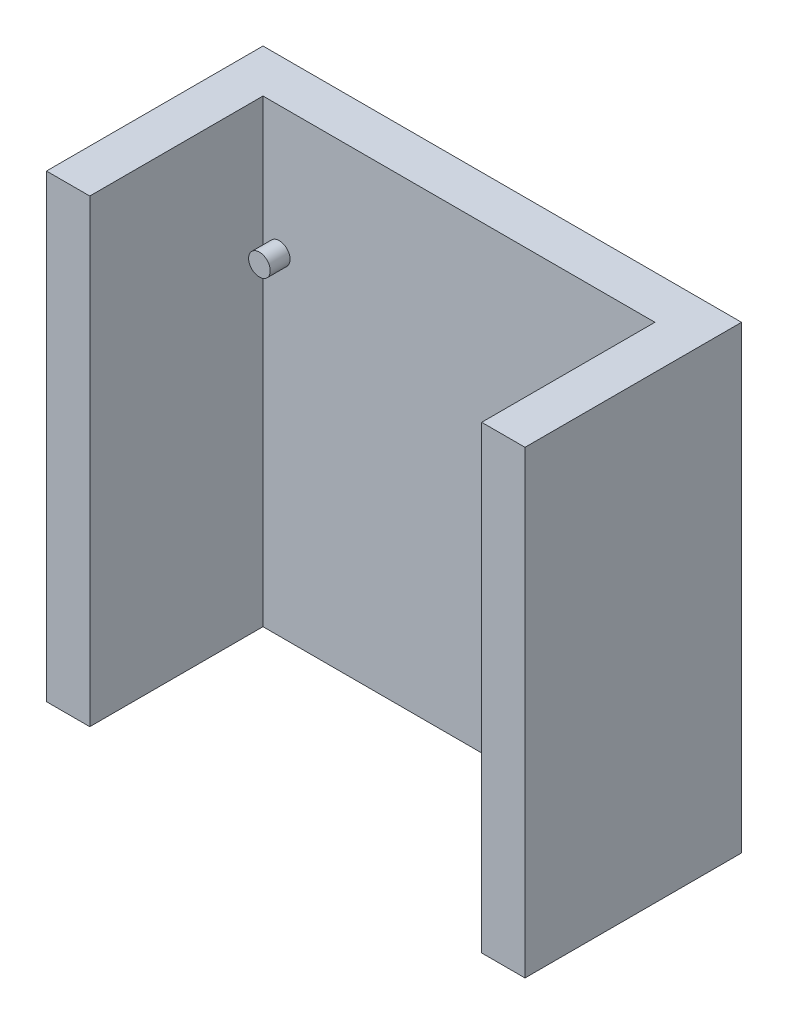
SolidWorks part; units mm, degrees
ref_plane "Front Plane" through (0, 0, 0) normal (0, 0, 1) x (1, 0, 0)
ref_plane "Top Plane" through (0, 0, 0) normal (0, 1, 0) x (1, 0, 0)
ref_plane "Right Plane" through (0, 0, 0) normal (1, 0, 0) x (0, 0, -1)
sketch "Sketch1" plane through (0, 0, 0) normal (1, 0, 0) x (0, 0, -1)
  line L0 (-145, 145) -> (-145, 255)
  line L2 (-145, 0) -> (-145, 145)
  line L3 (-145, 145) -> (0, 145) construction
  line L4 (0, 0) -> (0, 145)
  line L5 (-145, 255) -> (0, 255)
  line L6 (0, 255) -> (0, 145)
  line L7 (0, -145) -> (420.2376, 355.8197) construction
  line L8 (0, -145) -> (-93.2042, -33.9236) construction
  line L9 (94.1529, -32.793) -> (175.1688, -32.793) construction
  line L10 (-93.2042, -33.9236) -> (741.3522, 221.2259) construction
  line L11 (301.5271, 86.7579) -> (438.6224, 86.7579) construction
  line L12 (0, -145) -> (-176.7331, -199.0327) construction
  line L13 (-93.2042, -33.9236) -> (-193.8224, -153.8356) construction
  line L14 (274.6455, 249.3185) -> (274.6455, -80.6815)
  line L15 (274.6455, -80.6815) -> (168.3686, 167.5225)
  arc A0 (0, -145) -> (-145, 0) centre (0, 0) cw
  parabola Q0 (0, 0) -> (300.3031, 267.8046) focus (0, -145) apex (-49.0614, -159.9996)
  parabola Q1 (0, -145) -> (593.7614, 75.583) focus (-93.2042, -33.9236) apex (-147.8987, -99.1059)
  dimension "D1" = 145
  dimension "D2" = 110
  dimension "D3" = 50
  dimension "D4" = 17
  dimension "D5" = 80
  dimension "D6" = 330
  dimension "D7" = 270
sketch "Sketch2" plane through (0, 0, 0) normal (1, 0, 0) x (0, 0, -1)
  line L0 (-145, 145) -> (0, 145) construction
  line L1 (0, 255) -> (0, 145) construction
  line L2 (-145, 255) -> (0, 255) construction
  line L3 (-145, 145) -> (-145, 255) construction
  line L4 (274.6455, -80.6815) -> (168.3686, 167.5225) construction
  line L5 (274.6455, 249.3185) -> (274.6455, -80.6815) construction
  line L6 (0, 0) -> (0, 145) construction
  line L7 (-145, 0) -> (-145, 145) construction
  line L8 (-145, 145) -> (0, 145) construction
  line L9 (0, 255) -> (0, 145)
  line L10 (-145, 255) -> (0, 255)
  line L11 (-145, 145) -> (-145, 255)
  line L12 (274.6455, -80.6815) -> (168.3686, 167.5225)
  line L13 (274.6455, 249.3185) -> (274.6455, -80.6815) construction
  line L14 (0, 0) -> (0, 145)
  line L15 (-145, 0) -> (-145, 145)
  line L16 (-145.6, 0) -> (-145.6, 145)
  line L20 (0.6, 1.8139) -> (0.6, 145)
  line L21 (274.2922, 249.8034) -> (274.6455, 249.3185)
  line L22 (274.6455, -80.6815) -> (274.8642, -81.2403)
  line L23 (168.3686, 167.5225) -> (172.0457, 169.097)
  line L24 (168.3686, 167.5225) -> (274.6455, -80.6815)
  line L25 (172.0457, 169.097) -> (278.3226, -79.1071)
  line L26 (274.6455, -80.6815) -> (278.3226, -79.1071)
  line L27 (0, 145) -> (0.6, 145)
  line L28 (-145, 145) -> (-145.6, 145)
  line L29 (-155, 145) -> (-155, 265)
  line L30 (0.6, 255.6) -> (0.6, 145) construction
  line L31 (-145.6, 255.6) -> (0.6, 255.6) construction
  line L32 (-145.6, 145) -> (-145.6, 255.6) construction
  line L33 (-155, 265) -> (10, 265)
  line L34 (10, 265) -> (10, 145)
  line L35 (-155, 145) -> (-145, 145)
  line L36 (10, 145) -> (0, 145)
  line L38 (0, 145) -> (-145, 145)
  line L39 (0, 145) -> (0, 144.7)
  line L40 (0, 144.7) -> (-145, 144.7)
  line L41 (-145, 145) -> (-145, 144.7)
  arc A0 (-145, 0) -> (0, -145) centre (0, 0) ccw construction
  arc A1 (-145, 0) -> (0, -145) centre (0, 0) ccw
  arc A2 (-145.6, 0) -> (0, -145.6) centre (0, 0) ccw
  parabola Q0 (0, -145) -> (593.7614, 75.583) focus (-93.2042, -33.9236) apex (-147.8987, -99.1059) construction
  parabola Q1 (0, 0) -> (300.3031, 267.8046) focus (0, -145) apex (-49.0614, -159.9996) construction
  parabola Q2 (0, -145) -> (274.6455, -80.6815) focus (-93.2042, -33.9236) apex (-147.8987, -99.1059)
  parabola Q3 (0, 0) -> (274.6455, 249.3185) focus (0, -145) apex (-49.0614, -159.9996)
  spline S0 degree 1 poles (0, -145.6) (274.8642, -81.2403) knots 0 0 1 1 construction
  spline S1 degree 1 poles (0.6, 1.8139) (274.2922, 249.8034) knots 0 0 1 1 construction
  spline S2 degree 3 poles (274.8642, -81.2403) (273.1576, -81.9083) (269.7338, -83.2415) (262.9417, -85.8581) (254.5103, -89.0531) (244.501, -92.7603) (231.2945, -97.5361) (215.05, -103.1917) (195.9774, -109.4761) (177.3259, -115.2579) (153.0186, -122.2971) (123.6866, -129.8396) (90.1715, -136.8804) (63.6442, -141.072) (43.2642, -143.4196) (28.3972, -144.6775) (16.3662, -145.3064) (6.9341, -145.5581) (2.32, -145.6) (0, -145.6) knots 0.50387 0.50387 0.50387 0.50387 0.503942 0.504013 0.504156 0.5043 0.504443 0.504729 0.505015 0.505302 0.505588 0.506161 0.506734 0.507306 0.507593 0.507879 0.508165 0.508308 0.508452 0.508452 0.508452 0.508452
  spline S3 degree 3 poles (0.6, 1.8139) (1.4319, 2.9295) (3.0981, 5.1446) (6.5223, 9.6202) (10.937, 15.2496) (16.4614, 22.0765) (24.1255, 31.2688) (34.2669, 42.9303) (47.3338, 57.1972) (61.2981, 71.7376) (81.1138, 91.4895) (108.1271, 116.8637) (138.1321, 143.1509) (163.9312, 164.7288) (184.1782, 181.1862) (205.3228, 197.9178) (223.6912, 212.0892) (238.8352, 223.5637) (250.4165, 232.2373) (260.2579, 239.5249) (268.2359, 245.3839) (272.2758, 248.3346) (274.2922, 249.8034) knots 0.504877 0.504877 0.504877 0.504877 0.504963 0.505049 0.50522 0.505391 0.505563 0.505905 0.506248 0.50659 0.506933 0.507618 0.508303 0.508646 0.508989 0.509331 0.509674 0.509845 0.510016 0.510188 0.510273 0.510359 0.510359 0.510359 0.510359
  dimension "D2" = 4
  dimension "D4" = 0.3
  dimension "D1" = 0.6
  dimension "D3" = 10
sketch "Sketch3" plane through (0, 0, 0) normal (1, 0, 0) x (0, 0, -1)
  line L0 (274.6455, -80.6815) -> (168.3686, 167.5225) construction
  line L1 (168.3686, 167.5225) -> (172.0457, 169.097) construction
  line L2 (172.0457, 169.097) -> (278.3226, -79.1071) construction
  line L3 (274.6455, -80.6815) -> (278.3226, -79.1071) construction
  line L4 (168.3686, 167.5225) -> (274.6455, -80.6815) construction
  line L5 (0, 255) -> (0, 145) construction
  line L6 (-145, 255) -> (0, 255) construction
  line L7 (-145, 145) -> (-145, 255) construction
  line L8 (-145, 0) -> (-145, 145) construction
  line L9 (-145, 145) -> (-145.6, 145) construction
  line L10 (-145.6, 0) -> (-145.6, 145) construction
  line L11 (274.6455, -80.6815) -> (274.8642, -81.2403) construction
  line L12 (-155, 145) -> (-145, 145) construction
  line L13 (-155, 145) -> (-155, 265) construction
  line L14 (-155, 265) -> (10, 265) construction
  line L15 (10, 265) -> (10, 145) construction
  line L16 (10, 145) -> (0, 145) construction
  line L17 (0, 145) -> (-145, 145) construction
  line L18 (0, 145) -> (0, 144.7) construction
  line L19 (0, 144.7) -> (-145, 144.7) construction
  line L20 (-145, 145) -> (-145, 144.7) construction
  line L21 (0, 0) -> (0, 145) construction
  line L22 (274.2922, 249.8034) -> (274.6455, 249.3185) construction
  line L23 (0.6, 1.8139) -> (0.6, 145) construction
  line L24 (0, 145) -> (0.6, 145) construction
  line L25 (274.6455, -80.6815) -> (168.3686, 167.5225)
  line L26 (168.3686, 167.5225) -> (172.0457, 169.097)
  line L27 (172.0457, 169.097) -> (278.3226, -79.1071)
  line L28 (274.6455, -80.6815) -> (278.3226, -79.1071)
  line L29 (168.3686, 167.5225) -> (274.6455, -80.6815)
  line L30 (0, 255) -> (0, 145)
  line L31 (-145, 255) -> (0, 255)
  line L32 (-145, 145) -> (-145, 255)
  line L33 (-145, 0) -> (-145, 145)
  line L34 (-145, 145) -> (-145.6, 145)
  line L35 (-145.6, 0) -> (-145.6, 145)
  line L36 (274.6455, -80.6815) -> (274.8642, -81.2403)
  line L37 (-155, 145) -> (-145, 145)
  line L38 (-155, 145) -> (-155, 265)
  line L39 (-155, 265) -> (10, 265)
  line L40 (10, 265) -> (10, 145)
  line L41 (10, 145) -> (0, 145)
  line L42 (0, 145) -> (-145, 145)
  line L43 (0, 145) -> (0, 144.7)
  line L44 (0, 144.7) -> (-145, 144.7)
  line L45 (-145, 145) -> (-145, 144.7)
  line L46 (0, 0) -> (0, 145)
  line L47 (274.2922, 249.8034) -> (274.6455, 249.3185)
  line L48 (0.6, 1.8139) -> (0.6, 145)
  line L49 (0, 145) -> (0.6, 145)
  line L50 (-155, 575) -> (-155, 695)
  line L51 (-145, 575) -> (-145, 685)
  line L52 (-155, 695) -> (10, 695)
  line L53 (-145, 685) -> (0, 685)
  line L54 (10, 695) -> (10, 575)
  line L55 (0, 685) -> (0, 575)
  line L56 (10, 575) -> (0, 575)
  line L57 (0.6, 431.8139) -> (0.6, 575)
  line L58 (0, 430) -> (0, 575)
  line L59 (0, 574.7) -> (-145, 574.7)
  line L60 (-145, 430) -> (-145, 575)
  line L61 (-145.6, 430) -> (-145.6, 575)
  line L62 (-155, 575) -> (-145, 575)
  line L63 (274.6455, 349.3185) -> (274.8642, 348.7597)
  line L64 (274.6455, 349.3185) -> (278.3226, 350.8929)
  line L65 (274.6455, 349.3185) -> (168.3686, 597.5225)
  line L66 (172.0457, 599.097) -> (278.3226, 350.8929)
  line L67 (168.3686, 597.5225) -> (172.0457, 599.097)
  line L68 (274.2922, 679.8034) -> (274.6455, 679.3185)
  line L69 (0, 575) -> (-145, 575)
  line L70 (-155, 1005) -> (-155, 1125)
  line L71 (-145, 1005) -> (-145, 1115)
  line L72 (-155, 1125) -> (10, 1125)
  line L73 (-145, 1115) -> (0, 1115)
  line L74 (10, 1125) -> (10, 1005)
  line L75 (0, 1115) -> (0, 1005)
  line L76 (10, 1005) -> (0, 1005)
  line L77 (0.6, 861.8139) -> (0.6, 1005)
  line L78 (0, 860) -> (0, 1005)
  line L79 (0, 1004.7) -> (-145, 1004.7)
  line L80 (-145, 860) -> (-145, 1005)
  line L81 (-145.6, 860) -> (-145.6, 1005)
  line L82 (-155, 1005) -> (-145, 1005)
  line L83 (274.6455, 779.3185) -> (274.8642, 778.7597)
  line L84 (274.6455, 779.3185) -> (278.3226, 780.8929)
  line L85 (274.6455, 779.3185) -> (168.3686, 1027.5225)
  line L86 (172.0457, 1029.097) -> (278.3226, 780.8929)
  line L87 (168.3686, 1027.5225) -> (172.0457, 1029.097)
  line L88 (274.2922, 1109.8034) -> (274.6455, 1109.3185)
  line L89 (0, 1005) -> (-145, 1005)
  arc A0 (-145, 0) -> (0, -145) centre (0, 0) ccw construction
  arc A1 (-145.6, 0) -> (0, -145.6) centre (0, 0) ccw construction
  arc A2 (-145, 0) -> (0, -145) centre (0, 0) ccw
  arc A3 (-145.6, 0) -> (0, -145.6) centre (0, 0) ccw
  arc A4 (-145, 430) -> (0, 285) centre (0, 430) ccw
  arc A5 (-145.6, 430) -> (0, 284.4) centre (0, 430) ccw
  arc A6 (-145, 860) -> (0, 715) centre (0, 860) ccw
  arc A7 (-145.6, 860) -> (0, 714.4) centre (0, 860) ccw
  parabola Q0 (0, -145) -> (274.6455, -80.6815) focus (-93.2042, -33.9236) apex (-147.8987, -99.1059) construction
  parabola Q1 (0, 0) -> (274.6455, 249.3185) focus (0, -145) apex (-49.0614, -159.9996) construction
  parabola Q2 (0, -145) -> (274.6455, -80.6815) focus (-93.2042, -33.9236) apex (-147.8987, -99.1059)
  parabola Q3 (0, 0) -> (274.6455, 249.3185) focus (0, -145) apex (-49.0614, -159.9996)
  parabola Q4 (0, 430) -> (274.6455, 679.3185) focus (0, 285) apex (-49.0614, 270.0004)
  parabola Q5 (0, 285) -> (274.6455, 349.3185) focus (-93.2042, 396.0764) apex (-147.8987, 330.8941)
  parabola Q6 (0, 860) -> (274.6455, 1109.3185) focus (0, 715) apex (-49.0614, 700.0004)
  parabola Q7 (0, 715) -> (274.6455, 779.3185) focus (-93.2042, 826.0764) apex (-147.8987, 760.8941)
  spline S0 degree 3 poles (-2532.6565, -1138.1182) (517.166, 27.2131) (377.0621, -41.8945) (262.9417, -85.8581) (254.5103, -89.0531) (244.501, -92.7603) (231.2945, -97.5361) (215.05, -103.1917) (195.9774, -109.4761) (177.3259, -115.2579) (153.0186, -122.2971) (123.6866, -129.8396) (90.1715, -136.8804) (63.6442, -141.072) (43.2642, -143.4196) (28.3972, -144.6775) (16.3662, -145.3064) (-89.7923, -148.1384) (-144.0863, -112.0401) (-2997.9045, -39.5411) knots 0.499345 0.499345 0.499345 0.499345 0.503942 0.504013 0.504156 0.5043 0.504443 0.504729 0.505015 0.505302 0.505588 0.506161 0.506734 0.507306 0.507593 0.507879 0.508165 0.508308 0.514325 0.514325 0.514325 0.514325 only from (274.8642, -81.2403) to (0, -145.6) construction
  spline S1 degree 3 poles (-1751.4871, -2433.1925) (-55.1342, -100.2952) (-43.2482, -55.4331) (6.5223, 9.6202) (10.937, 15.2496) (16.4614, 22.0765) (24.1255, 31.2688) (34.2669, 42.9303) (47.3338, 57.1972) (61.2981, 71.7376) (81.1138, 91.4895) (108.1271, 116.8637) (138.1321, 143.1509) (163.9312, 164.7288) (184.1782, 181.1862) (205.3228, 197.9178) (223.6912, 212.0892) (238.8352, 223.5637) (250.4165, 232.2373) (260.2579, 239.5249) (377.9568, 325.9622) (533.0374, 426.7515) (-2133.1319, -1539.7711) knots 0.50024 0.50024 0.50024 0.50024 0.504963 0.505049 0.50522 0.505391 0.505563 0.505905 0.506248 0.50659 0.506933 0.507618 0.508303 0.508646 0.508989 0.509331 0.509674 0.509845 0.510016 0.510188 0.510273 0.515071 0.515071 0.515071 0.515071 only from (0.6, 1.8139) to (274.2922, 249.8034) construction
  spline S2 degree 3 poles (274.8642, -81.2403) (273.1576, -81.9083) (269.7338, -83.2415) (262.9417, -85.8581) (254.5103, -89.0531) (244.501, -92.7603) (231.2945, -97.5361) (215.05, -103.1917) (195.9774, -109.4761) (177.3259, -115.2579) (153.0186, -122.2971) (123.6866, -129.8396) (90.1715, -136.8804) (63.6442, -141.072) (43.2642, -143.4196) (28.3972, -144.6775) (16.3662, -145.3064) (6.9341, -145.5581) (2.32, -145.6) (0, -145.6) knots 0.50387 0.50387 0.50387 0.50387 0.503942 0.504013 0.504156 0.5043 0.504443 0.504729 0.505015 0.505302 0.505588 0.506161 0.506734 0.507306 0.507593 0.507879 0.508165 0.508308 0.508452 0.508452 0.508452 0.508452
  spline S3 degree 3 poles (0.6, 1.8139) (1.4319, 2.9295) (3.0981, 5.1446) (6.5223, 9.6202) (10.937, 15.2496) (16.4614, 22.0765) (24.1255, 31.2688) (34.2669, 42.9303) (47.3338, 57.1972) (61.2981, 71.7376) (81.1138, 91.4895) (108.1271, 116.8637) (138.1321, 143.1509) (163.9312, 164.7288) (184.1782, 181.1862) (205.3228, 197.9178) (223.6912, 212.0892) (238.8352, 223.5637) (250.4165, 232.2373) (260.2579, 239.5249) (268.2359, 245.3839) (272.2758, 248.3346) (274.2922, 249.8034) knots 0.504877 0.504877 0.504877 0.504877 0.504963 0.505049 0.50522 0.505391 0.505563 0.505905 0.506248 0.50659 0.506933 0.507618 0.508303 0.508646 0.508989 0.509331 0.509674 0.509845 0.510016 0.510188 0.510273 0.510359 0.510359 0.510359 0.510359
  spline S4 degree 3 poles (0.6, 431.8139) (1.4319, 432.9295) (3.0981, 435.1446) (6.5223, 439.6202) (10.937, 445.2496) (16.4614, 452.0765) (24.1255, 461.2688) (34.2669, 472.9303) (47.3338, 487.1972) (61.2981, 501.7376) (81.1138, 521.4895) (108.1271, 546.8637) (138.1321, 573.1509) (163.9312, 594.7288) (184.1782, 611.1862) (205.3228, 627.9178) (223.6912, 642.0892) (238.8352, 653.5637) (250.4165, 662.2373) (260.2579, 669.5249) (268.2359, 675.3839) (272.2758, 678.3346) (274.2922, 679.8034) knots 0.504877 0.504877 0.504877 0.504877 0.504963 0.505049 0.50522 0.505391 0.505563 0.505905 0.506248 0.50659 0.506933 0.507618 0.508303 0.508646 0.508989 0.509331 0.509674 0.509845 0.510016 0.510188 0.510273 0.510359 0.510359 0.510359 0.510359
  spline S5 degree 3 poles (274.8642, 348.7597) (273.1576, 348.0917) (269.7338, 346.7585) (262.9417, 344.1419) (254.5103, 340.9469) (244.501, 337.2397) (231.2945, 332.4639) (215.05, 326.8083) (195.9774, 320.5239) (177.3259, 314.7421) (153.0186, 307.7029) (123.6866, 300.1604) (90.1715, 293.1196) (63.6442, 288.928) (43.2642, 286.5804) (28.3972, 285.3225) (16.3662, 284.6936) (6.9341, 284.4419) (2.32, 284.4) (0, 284.4) knots 0.50387 0.50387 0.50387 0.50387 0.503942 0.504013 0.504156 0.5043 0.504443 0.504729 0.505015 0.505302 0.505588 0.506161 0.506734 0.507306 0.507593 0.507879 0.508165 0.508308 0.508452 0.508452 0.508452 0.508452
  spline S6 degree 3 poles (0.6, 861.8139) (1.4319, 862.9295) (3.0981, 865.1446) (6.5223, 869.6202) (10.937, 875.2496) (16.4614, 882.0765) (24.1255, 891.2688) (34.2669, 902.9303) (47.3338, 917.1972) (61.2981, 931.7376) (81.1138, 951.4895) (108.1271, 976.8637) (138.1321, 1003.1509) (163.9312, 1024.7288) (184.1782, 1041.1862) (205.3228, 1057.9178) (223.6912, 1072.0892) (238.8352, 1083.5637) (250.4165, 1092.2373) (260.2579, 1099.5249) (268.2359, 1105.3839) (272.2758, 1108.3346) (274.2922, 1109.8034) knots 0.504877 0.504877 0.504877 0.504877 0.504963 0.505049 0.50522 0.505391 0.505563 0.505905 0.506248 0.50659 0.506933 0.507618 0.508303 0.508646 0.508989 0.509331 0.509674 0.509845 0.510016 0.510188 0.510273 0.510359 0.510359 0.510359 0.510359
  spline S7 degree 3 poles (274.8642, 778.7597) (273.1576, 778.0917) (269.7338, 776.7585) (262.9417, 774.1419) (254.5103, 770.9469) (244.501, 767.2397) (231.2945, 762.4639) (215.05, 756.8083) (195.9774, 750.5239) (177.3259, 744.7421) (153.0186, 737.7029) (123.6866, 730.1604) (90.1715, 723.1196) (63.6442, 718.928) (43.2642, 716.5804) (28.3972, 715.3225) (16.3662, 714.6936) (6.9341, 714.4419) (2.32, 714.4) (0, 714.4) knots 0.50387 0.50387 0.50387 0.50387 0.503942 0.504013 0.504156 0.5043 0.504443 0.504729 0.505015 0.505302 0.505588 0.506161 0.506734 0.507306 0.507593 0.507879 0.508165 0.508308 0.508452 0.508452 0.508452 0.508452
  dimension "D1" = 3
extrude "Boss-Extrude1" add sketch "Sketch3" against normal blind 1250 contours S3 L48 L41 L43 L46 Q3 L47 | L41 L40 L39 L38 L37 L34 L32 L31 L30 | L44 L43 L42 L33 | S2 L36 Q2 A2 L33 L34 L35 A3 | L25 L28 L27 L26 | S5 L63 Q5 A4 L60 L62 L61 A5 | L67 L65 L64 L66 | S4 L57 L56 L58 Q4 L68 | L50 L62 L51 L53 L55 L56 L54 L52 | L58 L69 L60 L59 | L87 L85 L84 L86 | S7 L83 Q7 A6 L80 L82 L81 A7 | S6 L77 L76 L78 Q6 L88 | L78 L89 L80 L79 | L70 L82 L71 L73 L75 L76 L74 L72
sketch "Sketch4" plane through (0, 0, 0) normal (1, 0, 0) x (0, 0, -1)
  line L0 (-155, 1125) -> (10, 1125) construction
  line L1 (-180, 1150) -> (278.3226, 1150)
  line L2 (-180, 1150) -> (-180, -170.6)
  line L3 (-180, -170.6) -> (278.3226, -170.6)
  line L4 (278.3226, 1150) -> (278.3226, 1109.3185)
  line L5 (-155, 1005) -> (-155, 1125) construction
  line L6 (274.6455, 1109.3185) -> (278.3226, 1109.3185)
  line L7 (274.6455, 679.3185) -> (278.3226, 679.3185)
  line L8 (274.6455, 249.3185) -> (278.3226, 249.3185)
  line L9 (278.3226, 679.3185) -> (278.3226, 780.8929)
  line L10 (278.3226, -170.6) -> (278.3226, -79.1071)
  line L11 (278.3226, 249.3185) -> (278.3226, 350.8929)
  line L12 (274.6455, 1108.3185) -> (279.3226, 1108.3185)
  line L13 (279.3226, 1151) -> (279.3226, 1108.3185)
  line L14 (-181, 1151) -> (279.3226, 1151)
  line L15 (-181, 1151) -> (-181, -171.6)
  line L16 (-181, -171.6) -> (279.3226, -171.6)
  line L17 (279.3226, -171.6) -> (279.3226, -79.1071)
  line L18 (274.6455, 248.3185) -> (279.3226, 248.3185)
  line L19 (279.3226, 248.3185) -> (279.3226, 350.8929)
  line L20 (274.6455, 678.3185) -> (279.3226, 678.3185)
  line L21 (279.3226, 678.3185) -> (279.3226, 780.8929)
  line L22 (274.6455, 1108.3185) -> (274.6455, 1109.3185)
  line L23 (278.3226, 780.8929) -> (279.3226, 780.8929)
  line L24 (274.6455, 678.3185) -> (274.6455, 679.3185)
  line L25 (279.3226, 350.8929) -> (278.3226, 350.8929)
  line L26 (274.6455, 248.3185) -> (274.6455, 249.3185)
  line L27 (279.3226, -79.1071) -> (278.3226, -79.1071)
  dimension "D1" = 25
  dimension "D2" = 25
  dimension "D3" = 25
  dimension "D4" = 1
extrude "Boss-Extrude2" add sketch "Sketch4" against normal blind 1250 separate body
sketch "Sketch5" plane through (0, 0, 0) normal (1, 0, 0) x (0, 0, -1)
  line L1 (-181, 1151) -> (279.3226, 1151)
  line L2 (-181, 1151) -> (-181, -171.6)
  line L3 (-181, -171.6) -> (279.3226, -171.6)
  line L4 (279.3226, 1151) -> (279.3226, -171.6)
extrude "Boss-Extrude3" add sketch "Sketch5" along normal blind 10 separate body
sketch "Sketch6" plane through (-1250, 0, 0) normal (-1, 0, 0) x (0, 0, 1)
  line L4 (181, 1151) -> (-279.3226, 1151)
  line L5 (-279.3226, 1151) -> (-279.3226, -171.6)
  line L6 (-279.3226, -171.6) -> (181, -171.6)
  line L7 (181, -171.6) -> (181, 1151)
  line L8 (181, 1151) -> (-279.3226, 1151)
  line L9 (-279.3226, 1151) -> (-279.3226, -171.6)
  line L10 (-279.3226, -171.6) -> (181, -171.6)
  line L11 (181, -171.6) -> (181, 1151)
  dimension "D1" = 0
extrude "Boss-Extrude5" add sketch "Sketch6" along normal blind 10 separate body
sketch "Sketch7" plane through (10, 0, 0) normal (1, 0, 0) x (0, 0, -1)
  line L0 (-145, 145) -> (-145, 255) construction
  line L2 (-145, 255) -> (0, 255) construction
  circle A0 centre (-72.5, 200) radius 50
  circle A1 centre (-72.5, -53.7009) radius 50
  circle A2 centre (-72.5, 630) radius 50
  circle A3 centre (-72.5, 376.2991) radius 50
  circle A4 centre (-72.5, 1060) radius 50
  circle A5 centre (-72.5, 806.2991) radius 50
  dimension "D1" = 100
  dimension "D2" = 100
  dimension "D3" = 72.5
  dimension "D4" = 55
  dimension "D5" = 3
sketch "Sketch8" plane through (-1260, 0, 0) normal (-1, 0, 0) x (0, 0, 1)
  circle A1 centre (72.5, 1060) radius 50
  circle A2 centre (72.5, 1060) radius 50
  circle A3 centre (72.5, 376.2991) radius 50
  circle A4 centre (72.5, 376.2991) radius 50
  circle A5 centre (72.5, 630) radius 50
  circle A6 centre (72.5, 630) radius 50
  circle A7 centre (72.5, -53.7009) radius 50
  circle A8 centre (72.5, -53.7009) radius 50
  circle A9 centre (72.5, 200) radius 50
  circle A10 centre (72.5, 200) radius 50
  circle A11 centre (72.5, 806.2991) radius 50
  circle A12 centre (72.5, 806.2991) radius 50
  dimension "D1" = 0
  dimension "D2" = 0
  dimension "D3" = 0
  dimension "D4" = 0
  dimension "D5" = 0
  dimension "D6" = 0
ref_plane "Plane1" through (0, 0, 72.5) normal (0, 0, 1) x (1, 0, 0)
sketch "Sketch9" plane through (0, 0, 72.5) normal (0, 0, 1) x (1, 0, 0)
  line L0 (-1260, 200) -> (-1410, 200)
  line L2 (-1260, 250) -> (-1260, 150) construction
  line L3 (-1410, 200) -> (-1410, 376.2991)
  line L5 (-1410, 376.2991) -> (-1260, 376.2991)
  line L6 (-1260, 426.2991) -> (-1260, 326.2991) construction
  dimension "D1" = 150
sketch "Sketch10" plane through (-1260, 0, 0) normal (-1, 0, 0) x (0, 0, 1)
  circle A1 centre (72.5, 200) radius 50 construction
  circle A3 centre (72.5, 200) radius 50
sweep "Sweep3" add profiles "Sketch10" path "Sketch9"
sketch "Sketch11" plane through (0, 0, 72.5) normal (0, 0, 1) x (1, 0, 0)
  line L0 (10, 630) -> (160, 630)
  line L1 (160, 630) -> (160, 806.2991)
  line L2 (160, 806.2991) -> (10, 806.2991)
  dimension "D1" = 150
sketch "Sketch12" plane through (10, 0, 0) normal (1, 0, 0) x (0, 0, -1)
  circle A0 centre (-72.5, 630) radius 50 construction
  circle A1 centre (-72.5, 630) radius 50
sweep "Sweep4" add profiles "Sketch12" path "Sketch11"
sketch "Sketch14" plane through (10, 0, 0) normal (1, 0, 0) x (0, 0, -1)
  circle A0 centre (-72.5, -53.7009) radius 50 construction
  circle A1 centre (-72.5, -53.7009) radius 50
  circle A2 centre (-72.5, -53.7009) radius 51
  dimension "D1" = 102
ref_plane "Plane2" through (0, -53.7009, 0) normal (0, 1, 0) x (1, 0, 0)
sketch "Sketch15" plane through (0, -53.7009, 0) normal (0, 1, 0) x (1, 0, 0)
  line L0 (10, -72.5) -> (210, -72.5)
  line L1 (210, -72.5) -> (210, -472.5)
  dimension "D1" = 200
  dimension "D2" = 400
sweep "Sweep5" add profiles "Sketch14" path "Sketch15"
sketch "Sketch17" plane through (-1260, 0, 0) normal (-1, 0, 0) x (0, 0, 1)
  circle A0 centre (72.5, 1060) radius 50 construction
  circle A1 centre (72.5, 1060) radius 50
ref_plane "Plane3" through (0, 1060, 0) normal (0, 1, 0) x (1, 0, 0)
sketch "Sketch18" plane through (0, 1060, 0) normal (0, 1, 0) x (1, 0, 0)
  line L0 (-1260, -72.5) -> (-1460, -72.5)
  line L1 (-1460, -72.5) -> (-1460, -472.5)
  dimension "D1" = 200
  dimension "D2" = 400
sweep "Sweep6" add profiles "Sketch17" path "Sketch18"
sketch "Sketch13" plane through (0, 0, 181) normal (0, 0, 1) x (1, 0, 0)
  line L0 (-1250, 1151) -> (0, 1151) construction
  line L1 (-1535, 1651) -> (275, 1651)
  line L2 (-1535, 1651) -> (-1535, -471.6)
  line L3 (-1535, -471.6) -> (275, -471.6)
  line L4 (275, 1651) -> (275, -471.6)
  line L5 (-1250, -171.6) -> (0, -171.6) construction
  line L6 (-1260, -171.6) -> (-1260, 1151) construction
  line L7 (0, 1151) -> (0, -171.6) construction
  circle A1 centre (-1460, 1060) radius 50 construction
  circle A3 centre (-1460, 1060) radius 50
  circle A4 centre (210, -53.7009) radius 51 construction
  circle A5 centre (210, -53.7009) radius 51
  dimension "D1" = 500
  dimension "D2" = 300
  dimension "D3" = 275
  dimension "D4" = 275
extrude "Boss-Extrude6" add sketch "Sketch13" along normal blind 200
sketch "Sketch20" plane through (0, 1651, 0) normal (0, 1, 0) x (1, 0, 0)
  line L1 (-1535, -181) -> (-1735, -181)
  line L2 (-1535, -181) -> (-1535, -1181)
  line L3 (-1535, -1181) -> (-1735, -1181)
  line L4 (-1735, -181) -> (-1735, -1181)
  line L5 (275, -181) -> (475, -181)
  line L6 (275, -181) -> (275, -1181)
  line L7 (275, -1181) -> (475, -1181)
  line L8 (475, -181) -> (475, -1181)
  dimension "D1" = 200
  dimension "D2" = 1000
extrude "Boss-Extrude7" add sketch "Sketch20" against normal through all
